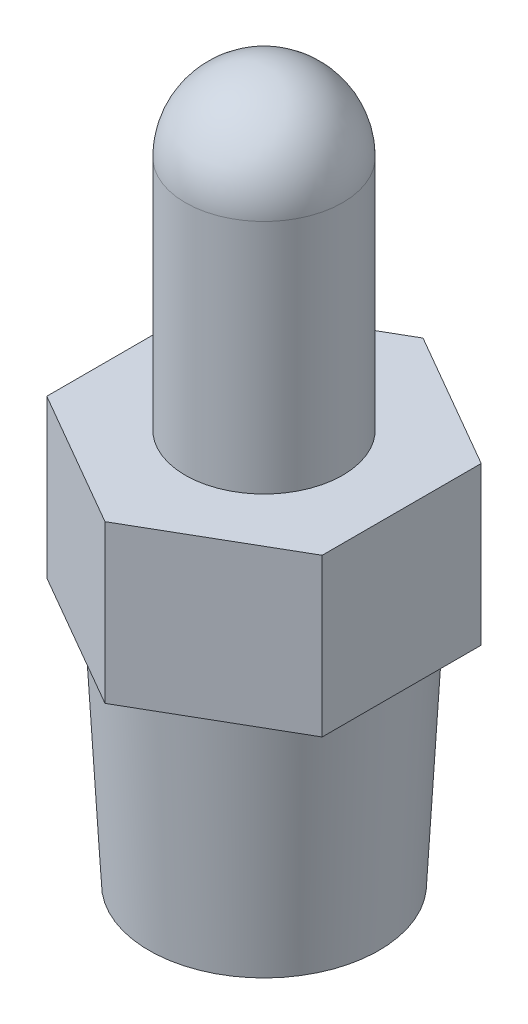
SolidWorks part; units mm, degrees
ref_plane "Front Plane" through (0, 0, 0) normal (0, 0, 1) x (1, 0, 0)
ref_plane "Top Plane" through (0, 0, 0) normal (0, 1, 0) x (1, 0, 0)
ref_plane "Right Plane" through (0, 0, 0) normal (1, 0, 0) x (0, 0, -1)
sketch "Sketch1" plane through (0, 0, 0) normal (0, 1, 0) x (1, 0, 0)
  line L1 (5.5562, 3.2079) -> (0, 6.4158)
  line L2 (0, 6.4158) -> (-5.5563, 3.2079)
  line L3 (-5.5563, 3.2079) -> (-5.5562, -3.2079)
  line L4 (-5.5562, -3.2079) -> (0, -6.4158)
  line L5 (0, -6.4158) -> (5.5563, -3.2079)
  line L6 (5.5563, -3.2079) -> (5.5562, 3.2079)
  circle A0 centre (0, 0) radius 5.5563 construction
  dimension "D1" = 11.1125
extrude "Boss-Extrude1" add sketch "Sketch1" along normal blind 6.35
sketch "Sketch3" plane through (0, 6.35, 0) normal (0, 1, 0) x (1, 0, 0)
  circle A0 centre (0, 0) radius 3.175
  dimension "D1" = 6.35
extrude "Boss-Extrude2" add sketch "Sketch3" along normal blind 12.7
fillet "Fillet1" radius 3.175 1 edges at (0, 19.05, 3.175)
sketch "Sketch4" plane through (0, 0, 0) normal (0, -1, 0) x (1, 0, 0)
  circle A0 centre (0, 0) radius 5.1368
extrude "Boss-Extrude3" add sketch "Sketch4" along normal blind 9.525 draft 3
